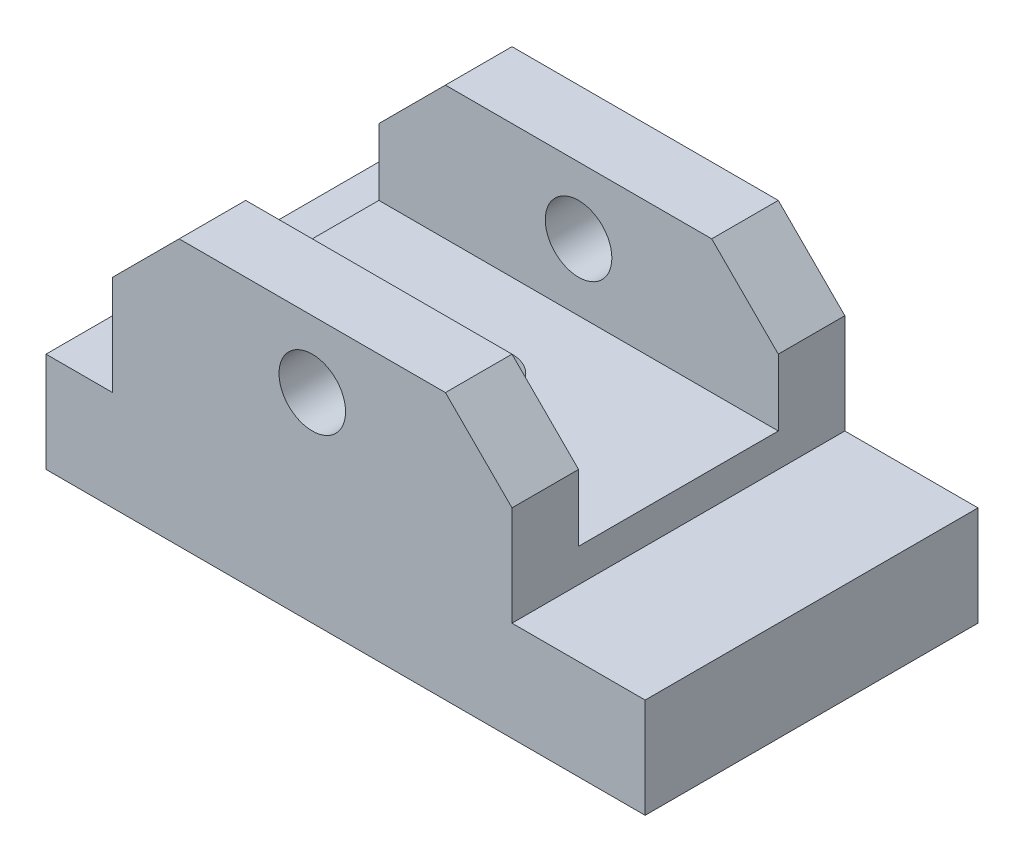
SolidWorks part; units mm, degrees
ref_plane "Front Plane" through (0, 0, 0) normal (0, 0, 1) x (1, 0, 0)
ref_plane "Top Plane" through (0, 0, 0) normal (0, 1, 0) x (1, 0, 0)
ref_plane "Right Plane" through (0, 0, 0) normal (1, 0, 0) x (0, 0, -1)
sketch "Sketch3" plane through (0, 0, 0) normal (0, 0, 1) x (1, 0, 0)
  line L0 (0, 0) -> (0, -15)
  line L1 (0, -15) -> (90, -15)
  line L2 (90, -15) -> (90, 0)
  line L3 (90, 0) -> (0, 0)
  line L4 (10, 0) -> (10, 15)
  line L5 (10, 15) -> (20, 25)
  line L6 (20, 25) -> (60, 25)
  line L7 (60, 25) -> (70, 15)
  line L8 (70, 15) -> (70, 0)
  line L9 (70, 0) -> (10, 0)
  dimension "D1" = 15
  dimension "D2" = 10
  dimension "D3" = 10
  dimension "D4" = 40
  dimension "D5" = 90
  dimension "D6" = 15
  dimension "D7" = 20
  dimension "D8" = 10
extrude "Boss-Extrude1" add sketch "Sketch3" along normal blind 50 contours L2 L3 L0 L1
sketch "Sketch5" plane through (0, 0, 50) normal (0, 0, 1) x (1, 0, 0)
  line L0 (10, 0) -> (10, 15)
  line L1 (90, 0) -> (0, 0) construction
  line L2 (10, 15) -> (20, 25)
  line L3 (20, 25) -> (60, 25)
  line L4 (60, 25) -> (70, 15)
  line L5 (70, 15) -> (70, 0)
  line L6 (70, 0) -> (10, 0)
  dimension "D1" = 40
  dimension "D2" = 20
  dimension "D3" = 15
  dimension "D4" = 10
  dimension "D5" = 10
extrude "Boss-Extrude2" add sketch "Sketch5" against normal blind 50
sketch "Sketch6" plane through (0, 25, 0) normal (0, 1, 0) x (1, 0, 0)
  line L0 (20, -10) -> (60, -10)
  line L1 (20, 0) -> (20, -50) construction
  line L2 (60, 0) -> (60, -50) construction
  line L3 (60, -10) -> (60, -40)
  line L4 (60, -40) -> (20, -40)
  line L5 (20, -40) -> (20, -10)
  dimension "D1" = 30
  dimension "D2" = 10
extrude "Cut-Extrude1" cut sketch "Sketch6" against normal blind 20
sketch "Sketch7" plane through (42.5, 42.5, 0) normal (0.7071, 0.7071, 0) x (0, 0, -1)
  line L0 (-40, -24.7487) -> (-40, -38.8909)
  line L1 (0, -38.8909) -> (-50, -38.8909) construction
  line L2 (-40, -38.8909) -> (-10, -38.8909)
  line L3 (-10, -38.8909) -> (-10, -24.7487)
  line L4 (-10, -24.7487) -> (-40, -24.7487)
  dimension "D1" = 30
extrude "Cut-Extrude2" cut sketch "Sketch7" against normal up to next and the other way through all
sketch "Sketch8" plane through (70, 0, 0) normal (1, 0, 0) x (0, 0, -1)
  line L0 (-40, 15) -> (-40, 5)
  line L1 (-40, 5) -> (-10, 5)
  line L2 (-10, 15) -> (-10, 5)
  line L3 (-10, 15) -> (-40, 15)
  dimension "D1" = 10
  dimension "D2" = 30
extrude "Cut-Extrude3" cut sketch "Sketch8" against normal through all both and the other way through all
sketch "Sketch9" plane through (-2.5, 2.5, 0) normal (-0.7071, 0.7071, 0) x (0, 0, 1)
  line L0 (10, 31.8198) -> (10, 17.6777)
  line L1 (10, 17.6777) -> (40, 17.6777)
  line L2 (40, 17.6777) -> (40, 31.8198)
  line L3 (40, 31.8198) -> (10, 31.8198)
extrude "Cut-Extrude4" cut sketch "Sketch9" against normal mid plane 21
sketch "Sketch10" plane through (0, 0, 50) normal (0, 0, 1) x (1, 0, 0)
  line L0 (60, 25) -> (20, 25) construction
  circle A0 centre (40, 15) radius 5
  point P4 (40, 25)
  dimension "D1" = 10
extrude "Cut-Extrude5" cut sketch "Sketch10" against normal through all both and the other way through all
sketch "Sketch11" plane through (0, 5, 0) normal (0, 1, 0) x (1, 0, 0)
  line L0 (10, -10) -> (10, -40) construction
  line L1 (10, 0) -> (10, -50) construction
  circle A0 centre (40, -25) radius 5
  point P4 (10, -25)
  dimension "D1" = 10
  dimension "D2" = 30
extrude "Cut-Extrude6" cut sketch "Sketch11" against normal through all both
sketch "Sketch12" plane through (0, 0, 50) normal (0, 0, 1) x (1, 0, 0)
  text T0 "ABHAY CIVIL D1\r\n25BCL048"
  point P1 (0, 0)
